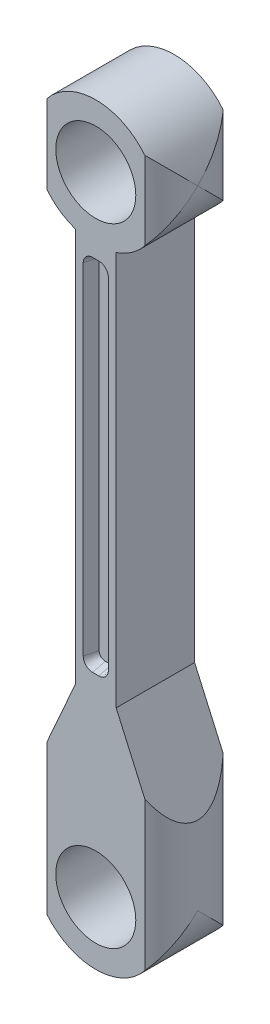
SolidWorks part; units mm, degrees
ref_plane "Front Plane" through (0, 0, 0) normal (0, 0, 1) x (1, 0, 0)
ref_plane "Top Plane" through (0, 0, 0) normal (0, 1, 0) x (1, 0, 0)
ref_plane "Right Plane" through (0, 0, 0) normal (1, 0, 0) x (0, 0, -1)
sketch "Sketch1" plane through (0, 0, 0) normal (0, 0, 1) x (1, 0, 0)
  line L0 (-10.16, 0) -> (-10.16, 12.7)
  line L1 (-10.16, 12.7) -> (-3.302, 28.176)
  line L2 (-3.302, 28.176) -> (-3.302, 91.9915)
  line L3 (10.16, 0) -> (10.16, 12.7)
  line L4 (10.16, 12.7) -> (3.302, 28.176)
  line L5 (3.302, 28.176) -> (3.302, 91.9915)
  circle A0 centre (0, 0) radius 6.477
  circle A1 centre (0, 101.6) radius 6.477
  arc A2 (3.302, 91.9915) -> (-3.302, 91.9915) centre (0, 101.6) ccw
  arc A3 (-10.16, 0) -> (10.16, 0) centre (0, 0) ccw
  point P5 (0, 0)
  point P6 (0, 0)
  point P13 (0, 0)
  point P16 (0, 0)
  point P17 (0, 0)
  point P18 (0, 0)
  dimension "D1" = 12.954
  dimension "D3" = 20.32
  dimension "D2" = 101.6
  dimension "D4" = 3.302
  dimension "D5" = 156.1
  dimension "D6" = 12.7
  dimension "D7" = 156.1
extrude "Boss-Extrude1" add sketch "Sketch1" along normal mid plane 12.7
sketch "Sketch2" plane through (0, 0, 0) normal (0, 0, 1) x (1, 0, 0)
  line L0 (3.302, 28.176) -> (3.302, 91.9915) construction
  line L1 (0.508, 31.242) -> (-0.508, 31.242)
  line L2 (2.032, 32.766) -> (2.032, 87.884)
  line L3 (0.508, 89.408) -> (-0.508, 89.408)
  line L4 (-2.032, 32.766) -> (-2.032, 87.884)
  line L5 (2.032, 31.242) -> (-2.032, 89.408) construction
  line L6 (2.032, 89.408) -> (-2.032, 31.242) construction
  line L7 (-3.302, 91.9915) -> (-3.302, 28.176) construction
  circle A0 centre (0, 101.6) radius 6.477 construction
  arc A1 (-2.032, 32.766) -> (-0.508, 31.242) centre (-0.508, 32.766) ccw
  arc A2 (0.508, 31.242) -> (2.032, 32.766) centre (0.508, 32.766) ccw
  arc A3 (2.032, 87.884) -> (0.508, 89.408) centre (0.508, 87.884) ccw
  arc A4 (-0.508, 89.408) -> (-2.032, 87.884) centre (-0.508, 87.884) ccw
  point P0 (0, 60.325)
  dimension "D5" = 1.524
  dimension "D1" = 31.242
  dimension "D2" = 12.192
  dimension "D3" = 1.27
  dimension "D4" = 1.27
extrude "Cut-Extrude4" cut sketch "Sketch2" against normal blind 2.032 draft 15 from surface at 6.35 starting at face at (6.477, 0, 6.35)
mirror "Mirror1" about plane through (0, 0, 0) normal (0, 0, 1) of "Cut-Extrude4"
sketch "Sketch3" plane through (0, 0, 0) normal (0, 1, 0) x (1, 0, 0)
  circle A0 centre (0, 0) radius 10.16
  dimension "D1" = 20.32
extrude "Cut-Extrude5" cut sketch "Sketch3" against normal through all both and the other way through all flip side to cut
